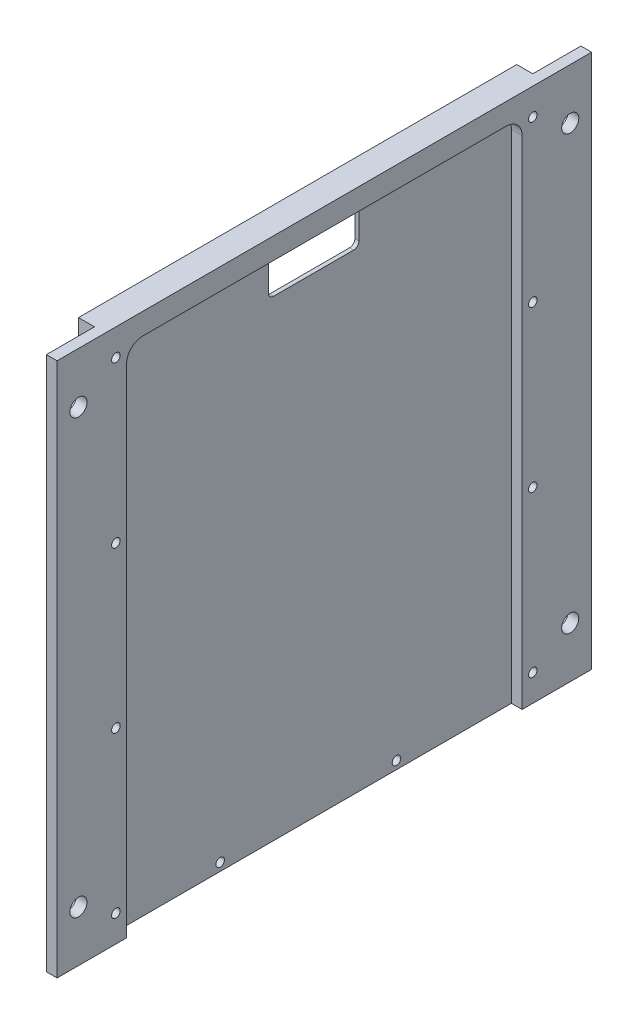
SolidWorks part; units mm, degrees
material "6061-T6 (SS)"
ref_plane "Front Plane" through (0, 0, 0) normal (0, 0, 1) x (1, 0, 0)
ref_plane "Top Plane" through (0, 0, 0) normal (0, 1, 0) x (1, 0, 0)
ref_plane "Right Plane" through (0, 0, 0) normal (1, 0, 0) x (0, 0, -1)
ref_plane "Plane1" through (4.25, 0, 0) normal (1, 0, 0) x (0, 0, -1)
sketch "Sketch1" plane through (4.25, 0, 0) normal (1, 0, 0) x (0, 0, -1)
  line L0 (-4.25, 0) -> (4.25, 0)
  line L1 (4.25, 0) -> (4.25, 227)
  line L2 (4.25, 227) -> (-4.25, 227)
  line L3 (-4.25, 227) -> (-4.25, 0)
  dimension "D1" = 227
  dimension "D2" = 8.5
  dimension "D3" = 4.25
  dimension "D4" = 227
extrude "Boss-Extrude1" add sketch "Sketch1" against normal blind 8.5
ref_plane "Plane2" through (-4.25, 0, 0) normal (-1, 0, 0) x (0, -1, 0)
sketch "Sketch2" plane through (-4.25, 0, 0) normal (-1, 0, 0) x (0, -1, 0)
  line L0 (-6.5, -87.25) -> (-6.5, -4.25)
  line L1 (-6.5, -4.25) -> (-220.5, -4.25)
  line L2 (-220.5, -4.25) -> (-220.5, -87.25)
  line L3 (-220.5, -87.25) -> (-227, -87.25)
  line L4 (-227, -87.25) -> (-227, -95.75)
  line L5 (-227, -95.75) -> (0, -95.75)
  line L6 (0, -95.75) -> (0, -87.25)
  line L7 (0, -87.25) -> (-6.5, -87.25)
  line L8 (0, -4.25) -> (-227, -4.25) construction
  dimension "D1" = 91.5
  dimension "D2" = 6.5
  dimension "D3" = 83
  dimension "D4" = 8.5
  dimension "D5" = 214
extrude "Boss-Extrude2" add sketch "Sketch2" against normal blind 2
sketch "Sketch3" plane through (-2.25, 0, 0) normal (1, 0, 0) x (0, 0, -1)
  line L0 (87.25, 0) -> (87.25, 227)
  line L1 (87.25, 227) -> (95.75, 227)
  line L2 (95.75, 227) -> (95.75, 0)
  line L3 (95.75, 0) -> (87.25, 0)
extrude "Boss-Extrude3" add sketch "Sketch3" along normal blind 6.5
ref_plane "Z_midplane" through (0, 113.5, 0) normal (0, 1, 0) x (1, 0, 0)
sketch "Sketch4" plane through (-4.25, 0, 0) normal (-1, 0, 0) x (0, 0, 1)
  line L0 (-4.75, 6.5) -> (-86.75, 6.5)
  line L1 (-86.75, 6.5) -> (-86.75, 220.5)
  line L2 (-86.75, 220.5) -> (-4.75, 220.5)
  line L3 (-4.75, 220.5) -> (-4.75, 6.5)
extrude "Boss-Extrude4" add sketch "Sketch4" along normal blind 3
sketch "Sketch5" plane through (-2.25, 0, 0) normal (1, 0, 0) x (0, 0, -1)
  line L0 (8.75, 10.5) -> (82.75, 10.5)
  line L1 (82.75, 10.5) -> (82.75, 216.5)
  line L2 (82.75, 216.5) -> (8.75, 216.5)
  line L3 (8.75, 216.5) -> (8.75, 10.5)
  line L4 (87.25, 6.5) -> (4.25, 6.5) construction
  line L5 (4.75, 6.5) -> (4.75, 220.5) construction
  line L6 (86.75, 220.5) -> (86.75, 6.5) construction
  line L7 (4.75, 220.5) -> (86.75, 220.5) construction
  dimension "D1" = 4
  dimension "D2" = 4
  dimension "D3" = 4
  dimension "D4" = 4
extrude "Cut-Extrude1" cut sketch "Sketch5" against normal through all
hole_wizard "M2x0.4 Tapped Hole1" positions "Sketch27" profile "Sketch26" tap size "M2x0.4" standard "ANSI Metric"
sketch "Sketch27" plane through (-7.25, 0, 0) normal (-1, 0, 0) x (0, 0, 1)
  line L0 (-86.75, 6.5) -> (-4.75, 6.5) construction
  line L2 (-45.75, 10.5) -> (-45.75, 216.5) construction
  line L3 (-8.75, 10.5) -> (-82.75, 10.5) construction
  line L4 (-82.75, 216.5) -> (-8.75, 216.5) construction
  line L6 (-8.75, 113.5) -> (-82.75, 113.5) construction
  line L7 (-8.75, 216.5) -> (-8.75, 10.5) construction
  line L8 (-82.75, 10.5) -> (-82.75, 216.5) construction
  line L9 (-8.75, 11.5) -> (-4.75, 11.5) construction
  line L10 (-4.75, 6.5) -> (-4.75, 220.5) construction
  point P0 (-6.75, 11.5)
  point P31 (-6.75, 41.5)
  point P32 (-6.75, 71.5)
  point P33 (-6.75, 101.5)
  point P54 (-84.75, 11.5)
  point P55 (-84.75, 41.5)
  point P56 (-84.75, 71.5)
  point P57 (-84.75, 101.5)
  point P60 (-84.75, 125.5)
  point P61 (-84.75, 155.5)
  point P62 (-84.75, 185.5)
  point P63 (-84.75, 215.5)
  point P65 (-6.75, 125.5)
  point P66 (-6.75, 155.5)
  point P67 (-6.75, 185.5)
  point P68 (-6.75, 215.5)
  point P81 (-6.75, 11.5)
  dimension "D1" = 5
  dimension "D4" = 30
  dimension "D3" = 4
sketch "Sketch26" plane through (-7.25, 11.5, -6.75) normal (0, 1, 0) x (0, 0, 1)
  line L0 (0, 0) -> (0, 11.5)
  line L1 (0, 11.5) -> (0.8, 11.5)
  line L2 (0.8, 11.5) -> (0.8, 0)
  line L5 (0.8, 0) -> (0, 0)
  line L11 (0, -6.35) -> (0, 107.95) construction
  dimension "Thru Tap Drill Dia." = 1.6
  dimension "Thru Tap Drill Depth" = 11.5
cosmetic thread "Hole Thread1" parameters "D2"=2
cosmetic thread "Hole Thread2" parameters "D2"=2
cosmetic thread "Hole Thread3" parameters "D2"=2
cosmetic thread "Hole Thread4" parameters "D2"=2
cosmetic thread "Hole Thread5" parameters "D2"=2
cosmetic thread "Hole Thread6" parameters "D2"=2
cosmetic thread "Hole Thread7" parameters "D2"=2
cosmetic thread "Hole Thread8" parameters "D2"=2
cosmetic thread "Hole Thread9" parameters "D2"=2
cosmetic thread "Hole Thread10" parameters "D2"=2
cosmetic thread "Hole Thread11" parameters "D2"=2
cosmetic thread "Hole Thread12" parameters "D2"=2
cosmetic thread "Hole Thread13" parameters "D2"=2
cosmetic thread "Hole Thread14" parameters "D2"=2
cosmetic thread "Hole Thread15" parameters "D2"=2
cosmetic thread "Hole Thread16" parameters "D2"=2
fillet "Fillet2" radius 3 4 edges at (-4.75, 10.5, -8.75) (-4.75, 216.5, -82.75) (-4.75, 216.5, -8.75) (-4.75, 10.5, -82.75)
fillet "Fillet12" radius 2 1 edges
ref_plane "Y_midplane" through (0, 0, -45.75) normal (0, 0, 1) x (1, 0, 0)
sketch "Sketch43" plane through (-7.25, 0, 0) normal (-1, 0, 0) x (0, 0, 1)
  line L0 (-45.75, 10.5) -> (-45.75, 216.5) construction
  line L1 (-27.75, 10.5) -> (-30.75, 10.5)
  line L2 (-27.75, 10.5) -> (-27.75, 216.5)
  line L3 (-27.75, 216.5) -> (-30.75, 216.5)
  line L4 (-30.75, 10.5) -> (-30.75, 216.5)
  line L5 (-11.75, 10.5) -> (-79.75, 10.5) construction
  line L6 (-79.75, 216.5) -> (-11.75, 216.5) construction
  line L7 (-63.75, 10.5) -> (-60.75, 10.5)
  line L8 (-63.75, 10.5) -> (-63.75, 216.5)
  line L9 (-63.75, 216.5) -> (-60.75, 216.5)
  line L10 (-60.75, 10.5) -> (-60.75, 216.5)
  dimension "D1" = 3
  dimension "D2" = 30
extrude "Boss-Extrude6" add sketch "Sketch43" against normal blind 3
sketch "Sketch44" plane through (-7.25, 0, 0) normal (-1, 0, 0) x (0, 0, 1)
  line L0 (-8.75, 213.5) -> (-8.75, 13.5) construction
  line L1 (-8.75, 35.8) -> (-82.75, 35.8)
  line L2 (-8.75, 35.8) -> (-8.75, 38.8)
  line L3 (-8.75, 38.8) -> (-82.75, 38.8)
  line L4 (-82.75, 35.8) -> (-82.75, 38.8)
  line L5 (-8.75, 75.8) -> (-82.75, 75.8)
  line L6 (-8.75, 75.8) -> (-8.75, 78.8)
  line L7 (-8.75, 78.8) -> (-82.75, 78.8)
  line L8 (-82.75, 75.8) -> (-82.75, 78.8)
  line L9 (-8.75, 103.5) -> (-82.75, 103.5)
  line L10 (-8.75, 103.5) -> (-8.75, 106.5)
  line L11 (-8.75, 106.5) -> (-82.75, 106.5)
  line L12 (-82.75, 103.5) -> (-82.75, 106.5)
  line L13 (-82.75, 13.5) -> (-82.75, 213.5) construction
  line L14 (-84.75, 6.5) -> (-4.75, 6.5) construction
  line L15 (-8.75, 113.5) -> (-82.75, 113.5) construction
  line L16 (-8.75, 191.2) -> (-8.75, 188.2)
  line L17 (-8.75, 191.2) -> (-82.75, 191.2)
  line L18 (-82.75, 191.2) -> (-82.75, 188.2)
  line L19 (-8.75, 188.2) -> (-82.75, 188.2)
  line L20 (-8.75, 151.2) -> (-8.75, 148.2)
  line L21 (-8.75, 151.2) -> (-82.75, 151.2)
  line L22 (-82.75, 151.2) -> (-82.75, 148.2)
  line L23 (-8.75, 148.2) -> (-82.75, 148.2)
  line L24 (-8.75, 123.5) -> (-8.75, 120.5)
  line L25 (-8.75, 123.5) -> (-82.75, 123.5)
  line L26 (-82.75, 123.5) -> (-82.75, 120.5)
  line L27 (-8.75, 120.5) -> (-82.75, 120.5)
  dimension "D1" = 3
  dimension "D2" = 29.3
  dimension "D3" = 40
  dimension "D4" = 100
extrude "Boss-Extrude7" add sketch "Sketch44" against normal up to surface (3 mm away)
fillet "Fillet4" radius 3 80 edges at (-5.75, 188.2, -8.75) (-5.75, 216.5, -60.75) (-5.75, 35.8, -82.75) (-5.75, 38.8, -82.75) (-5.75, 75.8, -82.75) (-5.75, 78.8, -82.75) (-5.75, 103.5, -82.75) (-5.75, 106.5, -82.75) (-5.75, 120.5, -82.75) (-5.75, 123.5, -82.75) (-5.75, 10.5, -60.75) (-5.75, 10.5, -63.75) (-5.75, 10.5, -27.75) (-5.75, 10.5, -30.75) (-5.75, 35.8, -8.75) (-5.75, 38.8, -8.75) (-5.75, 75.8, -8.75) (-5.75, 78.8, -8.75) (-5.75, 103.5, -8.75) (-5.75, 106.5, -8.75) (-5.75, 123.5, -8.75) (-5.75, 120.5, -8.75) (-5.75, 151.2, -8.75) (-5.75, 148.2, -8.75) (-5.75, 216.5, -27.75) (-5.75, 216.5, -63.75) (-5.75, 216.5, -30.75) (-5.75, 191.2, -8.75) (-5.75, 148.2, -82.75) (-5.75, 151.2, -82.75) (-5.75, 188.2, -82.75) (-5.75, 191.2, -82.75) (-5.75, 191.2, -60.75) (-5.75, 188.2, -60.75) (-5.75, 191.2, -63.75) (-5.75, 188.2, -63.75) (-5.75, 191.2, -27.75) (-5.75, 191.2, -30.75) (-5.75, 188.2, -27.75) (-5.75, 188.2, -30.75) (-5.75, 151.2, -27.75) (-5.75, 151.2, -30.75) (-5.75, 148.2, -27.75) (-5.75, 148.2, -30.75) (-5.75, 151.2, -60.75) (-5.75, 148.2, -60.75) (-5.75, 151.2, -63.75) (-5.75, 148.2, -63.75) (-5.75, 123.5, -27.75) (-5.75, 123.5, -30.75) (-5.75, 120.5, -27.75) (-5.75, 120.5, -30.75) (-5.75, 103.5, -27.75) (-5.75, 103.5, -30.75) (-5.75, 106.5, -27.75) (-5.75, 106.5, -30.75) (-5.75, 123.5, -60.75) (-5.75, 120.5, -60.75) (-5.75, 123.5, -63.75) (-5.75, 120.5, -63.75) (-5.75, 103.5, -60.75) (-5.75, 106.5, -60.75) (-5.75, 103.5, -63.75) (-5.75, 106.5, -63.75) (-5.75, 78.8, -30.75) (-5.75, 75.8, -27.75) (-5.75, 75.8, -30.75) (-5.75, 78.8, -27.75) (-5.75, 75.8, -60.75) (-5.75, 78.8, -60.75) (-5.75, 75.8, -63.75) (-5.75, 78.8, -63.75) (-5.75, 35.8, -27.75) (-5.75, 35.8, -30.75) (-5.75, 38.8, -27.75) (-5.75, 38.8, -30.75) (-5.75, 35.8, -63.75) (-5.75, 35.8, -60.75) (-5.75, 38.8, -63.75) (-5.75, 38.8, -60.75)
sketch "Sketch50" plane through (-4.25, 0, 0) normal (1, 0, 0) x (0, 0, -1)
  line L0 (79.75, 216.5) -> (11.75, 216.5) construction
  line L1 (8.75, 213.5) -> (8.75, 13.5) construction
  line L2 (11.75, 10.5) -> (79.75, 10.5) construction
  line L3 (82.75, 13.5) -> (82.75, 213.5) construction
  line L4 (79.75, 216.5) -> (11.75, 216.5)
  line L5 (8.75, 213.5) -> (8.75, 13.5)
  line L6 (11.75, 10.5) -> (79.75, 10.5)
  line L7 (82.75, 13.5) -> (82.75, 213.5)
  arc A0 (82.75, 213.5) -> (79.75, 216.5) centre (79.75, 213.5) ccw construction
  arc A1 (11.75, 216.5) -> (8.75, 213.5) centre (11.75, 213.5) ccw construction
  arc A2 (8.75, 13.5) -> (11.75, 10.5) centre (11.75, 13.5) ccw construction
  arc A3 (79.75, 10.5) -> (82.75, 13.5) centre (79.75, 13.5) ccw construction
  arc A4 (82.75, 213.5) -> (79.75, 216.5) centre (79.75, 213.5) ccw
  arc A5 (11.75, 216.5) -> (8.75, 213.5) centre (11.75, 213.5) ccw
  arc A6 (8.75, 13.5) -> (11.75, 10.5) centre (11.75, 13.5) ccw
  arc A7 (79.75, 10.5) -> (82.75, 13.5) centre (79.75, 13.5) ccw
extrude "webExtrude" add sketch "Sketch50" against normal blind 0.75
sketch "Sketch51" plane through (-5, 0, 0) normal (-1, 0, 0) x (0, 0, 1)
  line L0 (-57.75, 216.5) -> (-33.75, 216.5) construction
  line L1 (-54.225, 216.5) -> (-37.275, 216.5)
  line L2 (-54.225, 216.5) -> (-54.225, 208.7)
  line L3 (-54.225, 208.7) -> (-37.275, 208.7)
  line L4 (-37.275, 216.5) -> (-37.275, 208.7)
  point P4 (-45.75, 216.5)
  dimension "D1" = 7.8
  dimension "D2" = 16.95
extrude "12pinCutout" cut sketch "Sketch51" against normal through all both and the other way through all
mirror "Mirror10" about plane through (0, 113.5, 0) normal (0, 1, 0) of "12pinCutout"
fillet "Fillet18" radius 1 8 edges at (-4.625, 216.5, -37.275) (-4.625, 216.5, -54.225) (-4.625, 208.7, -54.225) (-4.625, 208.7, -37.275) (-4.625, 10.5, -37.275) (-4.625, 18.3, -37.275) (-4.625, 18.3, -54.225) (-4.625, 10.5, -54.225)
hole_wizard "M2x0.4 Tapped Hole2" positions "Sketch45" profile "Sketch46" tap size "M2x0.4" standard "ANSI Metric"
sketch "Sketch45" plane through (-7.25, 0, 0) normal (-1, 0, 0) x (0, 0, 1)
  line L0 (-44.75, 6.5) -> (-44.75, 220.5) construction
  line L1 (-84.75, 6.5) -> (-4.75, 6.5) construction
  line L20 (-4.75, 113.5) -> (-86.75, 113.5) construction
  line L21 (-4.75, 6.5) -> (-4.75, 220.5) construction
  line L23 (-62.25, 75.8) -> (-62.25, 78.8) construction
  line L24 (-79.75, 75.8) -> (-66.75, 75.8) construction
  line L25 (-66.75, 78.8) -> (-79.75, 78.8) construction
  line L27 (-60.75, 77.3) -> (-63.75, 77.3) construction
  line L28 (-60.75, 41.8) -> (-60.75, 72.8) construction
  line L29 (-63.75, 72.8) -> (-63.75, 41.8) construction
  line L30 (-79.75, 216.5) -> (-11.75, 216.5) construction
  line L31 (-87.25, 227) -> (-87.25, 0) construction
  point P2 (-61.25, 105)
  point P36 (-44.75, 6.5)
  point P68 (-28.25, 105)
  point P70 (-61.25, 122)
  point P71 (-28.25, 122)
  point P73 (-62.25, 77.3)
  point P92 (-27.25, 77.3)
  dimension "D1" = 4
  dimension "D2" = 0.5
  dimension "D3" = 16.5
  dimension "D4" = 17
sketch "Sketch46" plane through (-7.25, 105, -61.25) normal (0, 1, 0) x (0, 0, 1)
  line L0 (0, 0) -> (0, 11.5)
  line L1 (0, 11.5) -> (0.8, 11.5)
  line L2 (0.8, 11.5) -> (0.8, 0)
  line L5 (0.8, 0) -> (0, 0)
  line L11 (0, -6.35) -> (0, 107.95) construction
  dimension "Thru Tap Drill Dia." = 1.6
  dimension "Thru Tap Drill Depth" = 11.5
cosmetic thread "Hole Thread17" parameters "D2"=2
cosmetic thread "Hole Thread20" parameters "D2"=2
cosmetic thread "Hole Thread21" parameters "D2"=2
cosmetic thread "Hole Thread23" parameters "D2"=2
cosmetic thread "Hole Thread41" parameters "D2"=2
cosmetic thread "Hole Thread42" parameters "D2"=2
ref_plane "chamferStart" through (0, 212.5, 0) normal (0, 1, 0) x (1, 0, 0)
sketch "Sketch36" plane through (4.25, 0, 0) normal (1, 0, 0) x (0, 0, -1)
  line L1 (4.25, 207.45) -> (-1.25, 207.45)
  line L2 (4.25, 207.45) -> (4.25, 201.95)
  line L3 (4.25, 201.95) -> (-1.25, 201.95)
  line L4 (-1.25, 207.45) -> (-1.25, 201.95)
  line L5 (-4.25, 227) -> (-4.25, 0) construction
  line L6 (4.25, 207.45) -> (-1.25, 201.95) construction
  line L7 (4.25, 220.5) -> (87.25, 220.5) construction
  dimension "D1" = 13.05
  dimension "D2" = 5.5
  dimension "D3" = 5.5
  dimension "D4" = 8.5
extrude "Boss-Extrude5" add sketch "Sketch36" against normal up to surface (6.5 mm away)
ref_plane "Plane13" through (0, 113.5, 0) normal (0, 1, 0) x (1, 0, 0)
ref_plane "center_Y" through (0, 0, -45.75) normal (0, 0, 1) x (1, 0, 0)
ref_plane "center_Z" through (0, 113.5, 0) normal (0, 1, 0) x (1, 0, 0)
sketch "Sketch58" plane through (-2.25, 0, 0) normal (1, 0, 0) x (0, 0, -1)
  line L0 (11.75, 10.5) -> (79.75, 10.5) construction
  line L1 (43.25, 10.5) -> (48.25, 10.5)
  line L2 (43.25, 10.5) -> (43.25, 12)
  line L3 (43.25, 12) -> (48.25, 12)
  line L4 (48.25, 10.5) -> (48.25, 12)
  line L5 (87.25, 6.5) -> (4.25, 6.5) construction
  point P6 (45.75, 6.5)
  point P11 (45.75, 10.5)
  dimension "D1" = 5
  dimension "D2" = 5.5
extrude "Boss-Extrude9" add sketch "Sketch58" against normal up to surface (2.75 mm away)
sketch "Sketch63" plane through (0, 0, 0) normal (0, -1, 0) x (-1, 0, 0)
  line L1 (-4.25, 95.75) -> (7.9173, 95.75)
  line L2 (-4.25, 95.75) -> (-4.25, -4.25)
  line L3 (-4.25, -4.25) -> (7.9173, -4.25)
  line L4 (7.9173, 95.75) -> (7.9173, -4.25)
  dimension "D1" = 12.1673
  dimension "D2" = 100
extrude "Cut-Extrude28" cut sketch "Sketch63" against normal up to surface (120.5 mm away)
sketch "Sketch64" plane through (0, 227, 0) normal (0, 1, 0) x (1, 0, 0)
  line L1 (4.25, -4.25) -> (-12.9489, -4.25)
  line L2 (4.25, -4.25) -> (4.25, 100.8651)
  line L3 (4.25, 100.8651) -> (-12.9489, 100.8651)
  line L4 (-12.9489, -4.25) -> (-12.9489, 100.8651)
  dimension "D1" = 17.1989
  dimension "D2" = 105.1151
extrude "Cut-Extrude29" cut sketch "Sketch64" against normal up to surface (6.5 mm away)
sketch "Sketch65" plane through (0, 220.5, 0) normal (0, 1, 0) x (1, 0, 0)
  line L1 (4.25, 95.75) -> (-2.25, 95.75)
  line L2 (4.25, 95.75) -> (4.25, 87.25)
  line L3 (4.25, 87.25) -> (-2.25, 87.25)
  line L4 (-2.25, 95.75) -> (-2.25, 87.25)
  line L5 (4.25, -4.25) -> (-2.25, -4.25)
  line L6 (4.25, -4.25) -> (4.25, 4.25)
  line L7 (4.25, 4.25) -> (-2.25, 4.25)
  line L8 (-2.25, -4.25) -> (-2.25, 4.25)
extrude "Cut-Extrude30" cut sketch "Sketch65" against normal through all
sketch "Sketch70" plane through (-2.25, 0, 0) normal (1, 0, 0) x (0, 0, -1)
  line L2 (45.75, 220.5) -> (45.75, 120.5) construction
  line L3 (95.75, 120.5) -> (95.75, 220.5) construction
  line L4 (-4.25, 220.5) -> (95.75, 220.5) construction
  line L5 (82.75, 120.5) -> (8.75, 120.5) construction
  point P2 (91.75, 130)
  point P3 (91.75, 211)
  point P12 (-0.25, 130)
  point P13 (-0.25, 211)
  dimension "D5" = 4
  dimension "D6" = 4
  dimension "D8" = 81
hole_wizard "M3 Clearance Hole2" positions "Sketch71" profile "Sketch72" hole size "M3" standard "ISO"
sketch "Sketch71" plane through (-2.25, 0, 0) normal (1, 0, 0) x (0, 0, -1)
  point P6 (91.75, 211)
  point P9 (91.75, 130)
  point P12 (-0.25, 211)
  point P15 (-0.25, 130)
sketch "Sketch72" plane through (-2.25, 211, -91.75) normal (0, 1, 0) x (0, 0, -1)
  line L0 (0, 0) -> (0, 5)
  line L1 (0, 5) -> (1.6, 5)
  line L2 (1.6, 5) -> (1.6, 0)
  line L5 (1.6, 0) -> (0, 0)
  line L11 (0, -6.35) -> (0, 107.95) construction
  dimension "Thru Hole Dia." = 3.2
  dimension "Thru Hole Depth" = 5
equation "\"D2@Sketch56\"=\"D1@Sketch56\""
equation "\"D3@Sketch48\"=\"D2@Sketch48\""
